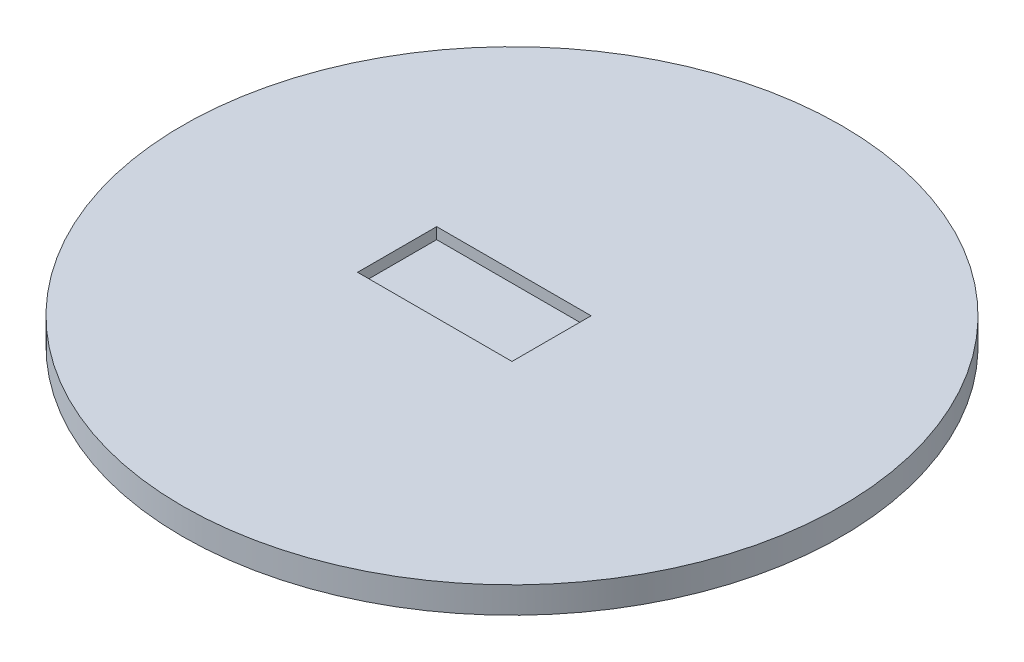
SolidWorks part; units mm, degrees
ref_plane "Front Plane" through (0, 0, 0) normal (0, 0, 1) x (1, 0, 0)
ref_plane "Top Plane" through (0, 0, 0) normal (0, 1, 0) x (1, 0, 0)
ref_plane "Right Plane" through (0, 0, 0) normal (1, 0, 0) x (0, 0, -1)
sketch "Sketch1" plane through (0, 0, 0) normal (0, 1, 0) x (1, 0, 0)
  circle A0 centre (0, 0) radius 87.5
  dimension "D1" = 175
extrude "Boss-Extrude1" add sketch "Sketch1" along normal blind 7
sketch "Sketch2" plane through (0, 7, 0) normal (0, 1, 0) x (1, 0, 0)
  line L0 (-3.85, 0) -> (3.85, 0) construction
  line L1 (-30.5, 10.5) -> (10.5, 10.5)
  line L2 (-30.5, 10.5) -> (-30.5, -10.5)
  line L3 (-30.5, -10.5) -> (10.5, -10.5)
  line L4 (10.5, 10.5) -> (10.5, -10.5)
  line L5 (-30.5, 10.5) -> (10.5, -10.5) construction
  line L6 (-30.5, -10.5) -> (10.5, 10.5) construction
  point P0 (-10, 0)
  dimension "D1" = 41
  dimension "D2" = 21
  dimension "D3" = 10
extrude "Cut-Extrude1" cut sketch "Sketch2" against normal blind 3
